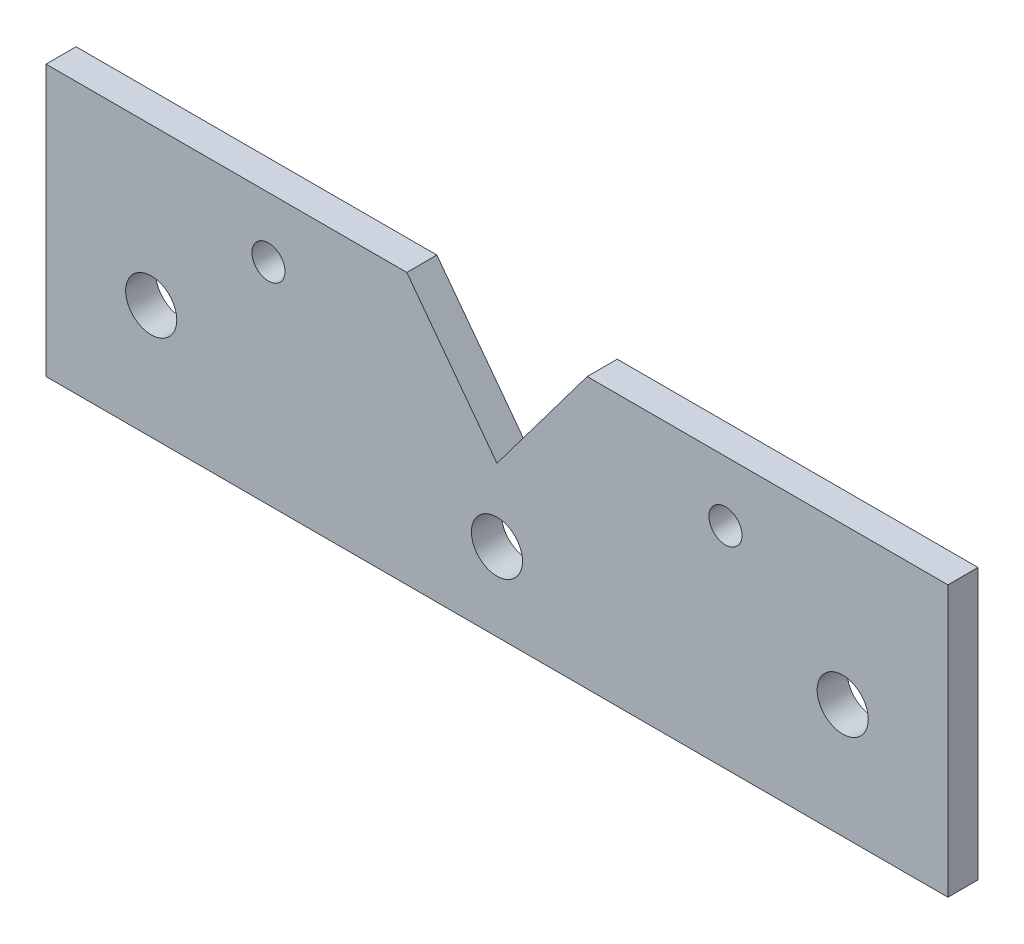
SolidWorks part; units mm, degrees
ref_plane "Front Plane" through (0, 0, 0) normal (0, 0, 1) x (1, 0, 0)
ref_plane "Top Plane" through (0, 0, 0) normal (0, 1, 0) x (1, 0, 0)
ref_plane "Right Plane" through (0, 0, 0) normal (1, 0, 0) x (0, 0, -1)
sketch "Sketch1" plane through (0, 0, 0) normal (0, 0, 1) x (1, 0, 0)
  line L0 (-127.4992, 23.5261) -> (-127.4992, 68.5261)
  line L1 (-127.4992, 68.5261) -> (-67.4992, 68.5261)
  line L2 (-67.4992, 68.5261) -> (-52.4992, 48.5261)
  line L3 (-52.4992, 48.5261) -> (-37.4992, 68.5261)
  line L4 (-37.4992, 68.5261) -> (22.5008, 68.5261)
  line L5 (22.5008, 68.5261) -> (22.5008, 23.5261)
  line L6 (22.5008, 23.5261) -> (-127.4992, 23.5261)
  line L7 (-52.4992, 48.5261) -> (-52.4992, 23.5261) construction
  line L8 (-127.4992, 36.5261) -> (22.5008, 36.5261) construction
  line L9 (-127.4992, 42.5261) -> (22.5008, 42.5261) construction
  circle A0 centre (-109.9992, 42.5261) radius 4.25
  circle A1 centre (5.0008, 42.5261) radius 4.25
  circle A2 centre (-52.4992, 36.5261) radius 4.25
  circle A3 centre (-90.4992, 58.5261) radius 2.75
  circle A4 centre (-14.4992, 58.5261) radius 2.75
  point P2 (-52.4992, 23.5261)
  dimension "D5" = 8.5
  dimension "D6" = 8.5
  dimension "D7" = 8.5
  dimension "D16" = 5.5
  dimension "D17" = 5.5
  dimension "D1" = 45
  dimension "D2" = 150
  dimension "D3" = 20
  dimension "D4" = 30
  dimension "D8" = 57.5
  dimension "D9" = 57.5
  dimension "D10" = 13
  dimension "D11" = 19
  dimension "D12" = 38
  dimension "D13" = 38
  dimension "D14" = 35
  dimension "D15" = 35
extrude "Boss-Extrude1" add sketch "Sketch1" along normal blind 5
